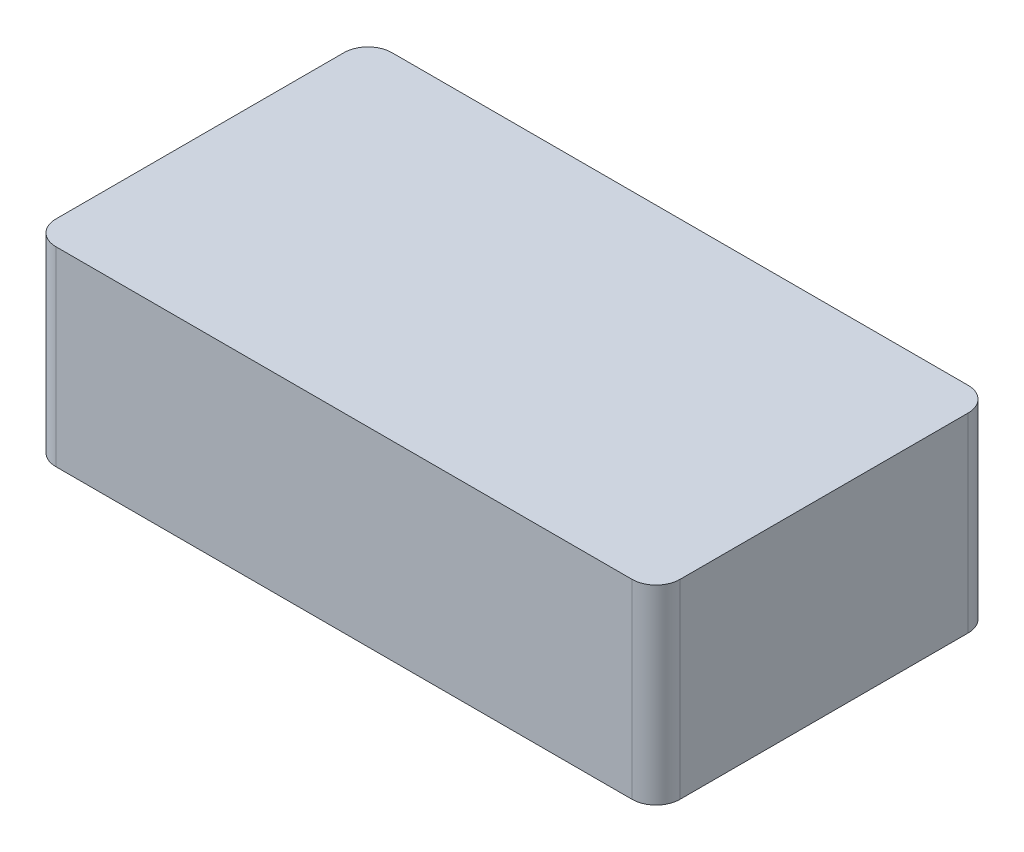
SolidWorks part; units mm, degrees
ref_plane "前基準面" through (0, 0, 0) normal (0, 0, 1) x (1, 0, 0)
ref_plane "上基準面" through (0, 0, 0) normal (0, 1, 0) x (1, 0, 0)
ref_plane "右基準面" through (0, 0, 0) normal (1, 0, 0) x (0, 0, -1)
sketch "Sketch1" plane through (0, 0, 0) normal (0, 1, 0) x (1, 0, 0)
  line L1 (0, 0) -> (6.5, 0)
  line L2 (0, 0) -> (0, 3.5)
  line L3 (0, 3.5) -> (6.5, 3.5)
  line L4 (6.5, 0) -> (6.5, 3.5)
  dimension "D1" = 3.5
  dimension "D2" = 6.5
extrude "Boss-Extrude1" add sketch "Sketch1" along normal blind 1.9844
fillet "Fillet1" radius 0.25 2 edges at (6.5, 0.9922, 0) (0, 0.9922, 0)
fillet "Fillet2" radius 0.25 2 edges at (6.5, 0.9922, -3.5) (0, 0.9922, -3.5)
